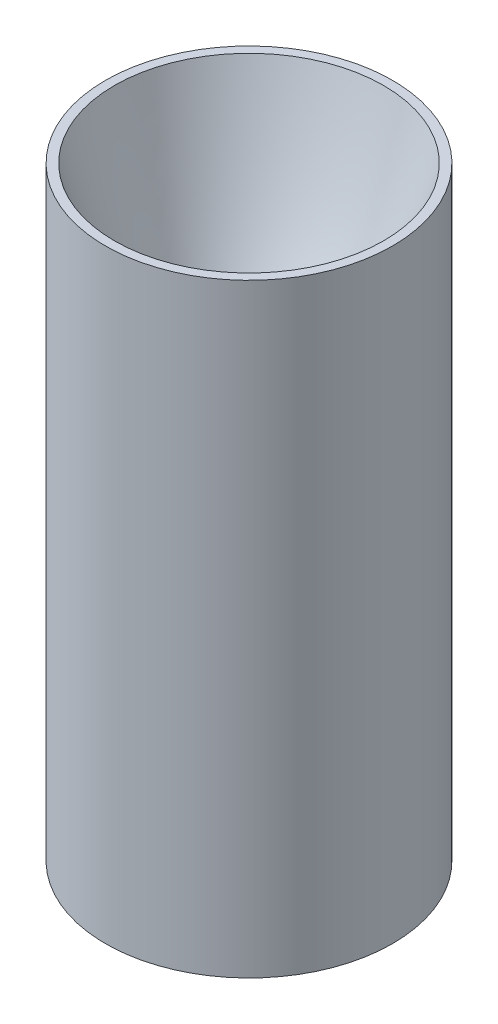
SolidWorks part; units mm, degrees
material "AISI 1020"
ref_plane "Front Plane" through (0, 0, 0) normal (0, 0, 1) x (1, 0, 0)
ref_plane "Top Plane" through (0, 0, 0) normal (0, 1, 0) x (1, 0, 0)
ref_plane "Right Plane" through (0, 0, 0) normal (1, 0, 0) x (0, 0, -1)
sketch "Sketch1" plane through (0, 0, 0) normal (0, 0, 1) x (1, 0, 0)
  line L0 (-0.0055, 165.816) -> (-0.0055, -134.6871) construction
  line L1 (71.7275, 109.9275) -> (76.49, 109.9275)
  line L4 (53.8815, -59.7275) -> (53.8815, -212.1275)
  line L9 (76.49, 109.9275) -> (76.49, -212.1275)
  line L10 (76.49, -212.1275) -> (53.8815, -212.1275)
  spline S0 degree 2 poles (26.7953, 6.5094) (49.2614, 34.6361) (71.7275, 109.9275) knots 0 0 0 1 1 1 construction
  spline S1 degree 2 poles (26.7953, 6.5094) (49.2614, 34.6361) (71.7275, 109.9275) knots 0 0 0 1 1 1
  spline S2 degree 4 poles (24.1269, -0.7179) (24.126, -0.7018) (24.1243, -0.6738) (24.121, -0.6546) (24.115, -0.5166) (24.1058, -0.4369) (24.0994, -0.1066) (24.0979, 0.0018) (24.102, 0.2678) (24.1085, 0.4272) (24.1205, 0.6469) (24.1414, 0.9016) (24.1752, 1.2027) (24.2265, 1.5422) (24.2905, 1.8812) (24.3671, 2.2165) (24.4563, 2.5494) (24.5577, 2.8783) (24.6716, 3.2035) (24.7972, 3.5238) (24.9353, 3.8398) (25.0841, 4.1494) (25.246, 4.4549) (25.4165, 4.7515) (25.6025, 5.0459) (25.7918, 5.3257) (26.0044, 5.6109) (26.1789, 5.8331) (26.3663, 6.0501) (26.5046, 6.2088) (26.757, 6.4728) (26.837, 6.5526) (27.1016, 6.806) (27.1881, 6.8783) (27.2854, 6.9667) (27.3038, 6.9803) (27.3264, 7.0004) knots 0 0 0 0 0 0.005192 0.010384 0.020768 0.041536 0.082569 0.102427 0.122284 0.142142 0.162 0.201716 0.241431 0.281147 0.320863 0.360578 0.400294 0.44001 0.479725 0.519441 0.559156 0.598872 0.638588 0.678303 0.718019 0.757735 0.79745 0.837166 0.857024 0.876882 0.916597 0.958047 0.979024 0.989512 1 1 1 1 1 construction
  spline S3 degree 4 poles (24.0991, 0.0002) (24.0991, 0.0361) (24.0996, 0.1103) (24.102, 0.2678) (24.1085, 0.4272) (24.1205, 0.6469) (24.1414, 0.9016) (24.1752, 1.2027) (24.2265, 1.5422) (24.2905, 1.8812) (24.3671, 2.2165) (24.4563, 2.5494) (24.5577, 2.8783) (24.6716, 3.2035) (24.7972, 3.5238) (24.9353, 3.8398) (25.0841, 4.1494) (25.246, 4.4549) (25.4165, 4.7515) (25.6025, 5.0459) (25.7918, 5.3257) (26.0044, 5.6109) (26.1789, 5.8331) (26.3663, 6.0501) (26.5046, 6.2088) (26.6704, 6.3823) (26.7445, 6.4586) (26.7953, 6.5094) knots 0.082569 0.082569 0.082569 0.082569 0.082569 0.102427 0.122284 0.142142 0.162 0.201716 0.241431 0.281147 0.320863 0.360578 0.400294 0.44001 0.479725 0.519441 0.559156 0.598872 0.638588 0.678303 0.718019 0.757735 0.79745 0.837166 0.857024 0.876882 0.916597 0.916597 0.916597 0.916597 0.916597
  spline S4 degree 4 poles (24.2082, 2.808) (24.2014, 2.7166) (24.1882, 2.5518) (24.1642, 2.1754) (24.1352, 1.6881) (24.1148, 1.1018) (24.103, 0.6556) (24.0988, 0.1104) (24.0988, -0.0999) (24.102, -0.543) (24.1083, -0.824) (24.1178, -1.1947) (24.1304, -1.5133) (24.1462, -1.8618) (24.1652, -2.1935) (24.1928, -2.6179) (24.2323, -3.1219) (24.3033, -3.8798) (24.4231, -4.8863) (24.5995, -6.0566) (24.8509, -7.385) (25.1518, -8.7034) (25.5018, -10.0095) (25.9004, -11.3017) (26.3469, -12.5779) (26.841, -13.8367) (27.3817, -15.076) (27.9685, -16.2944) (28.6001, -17.4898) (29.2765, -18.6611) (29.9954, -19.8056) (30.758, -20.9237) (31.4592, -21.8743) (32.0887, -22.6733) (32.6241, -23.3203) (33.0723, -23.8398) (33.5085, -24.3297) (33.9358, -24.7883) (34.2456, -25.1137) (34.6121, -25.4859) (34.7661, -25.6398) (35.1509, -26.0187) (35.4776, -26.3286) (35.905, -26.7273) (36.2395, -27.0242) (36.5192, -27.2707) (36.6465, -27.3798) (36.7148, -27.4387) (36.7496, -27.4686) knots 0 0 0 0 0 0.010393 0.020785 0.041571 0.062104 0.072371 0.082638 0.092575 0.102512 0.112449 0.122387 0.132324 0.142261 0.152198 0.162135 0.18201 0.201884 0.241633 0.281382 0.32113 0.360879 0.400628 0.440377 0.480126 0.519874 0.559623 0.599372 0.639121 0.67887 0.718618 0.758367 0.798116 0.81799 0.837865 0.857739 0.877613 0.897488 0.907425 0.917362 0.927629 0.937896 0.958429 0.979215 0.989607 0.994804 1 1 1 1 1 construction
  spline S5 degree 4 poles (24.0991, 0.0002) (24.0991, -0.0704) (24.0996, -0.2134) (24.102, -0.543) (24.1083, -0.824) (24.1178, -1.1947) (24.1304, -1.5133) (24.1462, -1.8618) (24.1652, -2.1935) (24.1928, -2.6179) (24.2323, -3.1219) (24.3033, -3.8798) (24.4231, -4.8863) (24.5995, -6.0566) (24.8509, -7.385) (25.1518, -8.7034) (25.5018, -10.0095) (25.9004, -11.3017) (26.3469, -12.5779) (26.841, -13.8367) (27.3817, -15.076) (27.9685, -16.2944) (28.6001, -17.4898) (29.2765, -18.6611) (29.9954, -19.8056) (30.758, -20.9237) (31.4592, -21.8743) (32.0887, -22.6733) (32.6241, -23.3203) (33.0723, -23.8398) (33.5085, -24.3297) (33.9358, -24.7883) (34.2456, -25.1137) (34.5369, -25.4095) (34.6364, -25.5098) (34.6863, -25.5597) knots 0.082638 0.082638 0.082638 0.082638 0.082638 0.092575 0.102512 0.112449 0.122387 0.132324 0.142261 0.152198 0.162135 0.18201 0.201884 0.241633 0.281382 0.32113 0.360879 0.400628 0.440377 0.480126 0.519874 0.559623 0.599372 0.639121 0.67887 0.718618 0.758367 0.798116 0.81799 0.837865 0.857739 0.877613 0.897488 0.907425 0.917362 0.917362 0.917362 0.917362 0.917362
  spline S6 degree 1 poles (34.6863, -25.5597) (43.2939, -34.1673) knots 0 0 1 1 construction
  spline S7 degree 1 poles (34.6863, -25.5597) (43.2939, -34.1673) knots 0 0 1 1
  spline S8 degree 4 poles (53.7724, -62.5352) (53.7792, -62.4464) (53.7924, -62.2737) (53.8104, -62.0016) (53.8309, -61.6599) (53.848, -61.2921) (53.8616, -60.9658) (53.8717, -60.5752) (53.8784, -60.2939) (53.8818, -59.8332) (53.8818, -59.6304) (53.8786, -59.1816) (53.8723, -58.9048) (53.8628, -58.5326) (53.8502, -58.2128) (53.8304, -57.7816) (53.8004, -57.281) (53.7562, -56.688) (53.6773, -55.8485) (53.5774, -55.0082) (53.4567, -54.1724) (53.2868, -53.1724) (53.0921, -52.1774) (52.8664, -51.1885) (52.61, -50.2075) (52.3293, -49.2331) (52.0243, -48.266) (51.6335, -47.1491) (51.1395, -45.8904) (50.5987, -44.651) (50.0121, -43.4327) (49.3801, -42.2371) (48.7041, -41.0662) (47.9845, -39.921) (47.2231, -38.8041) (46.5199, -37.8515) (45.8935, -37.0557) (45.3528, -36.4034) (44.9151, -35.8942) (44.5148, -35.447) (44.1815, -35.0846) (43.8739, -34.7603) (43.6741, -34.5515) (43.3653, -34.2383) (43.2159, -34.0889) (42.8277, -33.7066) (42.5041, -33.3998) (42.0741, -32.9986) (41.7412, -32.7033) (41.4607, -32.4559) (41.3338, -32.3472) (41.2653, -32.2883) (41.2305, -32.2583) knots 0 0 0 0 0 0.010393 0.020785 0.031178 0.041571 0.051838 0.062104 0.072371 0.082638 0.092575 0.102512 0.112449 0.122387 0.132324 0.142261 0.162135 0.18201 0.201884 0.241633 0.261507 0.281382 0.32113 0.360879 0.380754 0.400628 0.440377 0.480126 0.519874 0.559623 0.599372 0.639121 0.67887 0.718618 0.758367 0.798116 0.81799 0.837865 0.857739 0.877613 0.887551 0.897488 0.907425 0.917362 0.927629 0.937896 0.958429 0.979215 0.989607 0.994804 1 1 1 1 1 construction
  spline S9 degree 4 poles (53.8815, -59.7275) (53.8815, -59.657) (53.881, -59.5154) (53.8786, -59.1816) (53.8723, -58.9048) (53.8628, -58.5326) (53.8502, -58.2128) (53.8304, -57.7816) (53.8004, -57.281) (53.7562, -56.688) (53.6773, -55.8485) (53.5774, -55.0082) (53.4567, -54.1724) (53.2868, -53.1724) (53.0921, -52.1774) (52.8664, -51.1885) (52.61, -50.2075) (52.3293, -49.2331) (52.0243, -48.266) (51.6335, -47.1491) (51.1395, -45.8904) (50.5987, -44.651) (50.0121, -43.4327) (49.3801, -42.2371) (48.7041, -41.0662) (47.9845, -39.921) (47.2231, -38.8041) (46.5199, -37.8515) (45.8935, -37.0557) (45.3528, -36.4034) (44.9151, -35.8942) (44.5148, -35.447) (44.1815, -35.0846) (43.8739, -34.7603) (43.6741, -34.5515) (43.4444, -34.3185) (43.3438, -34.2172) (43.2939, -34.1673) knots 0.082638 0.082638 0.082638 0.082638 0.082638 0.092575 0.102512 0.112449 0.122387 0.132324 0.142261 0.162135 0.18201 0.201884 0.241633 0.261507 0.281382 0.32113 0.360879 0.380754 0.400628 0.440377 0.480126 0.519874 0.559623 0.599372 0.639121 0.67887 0.718618 0.758367 0.798116 0.81799 0.837865 0.857739 0.877613 0.887551 0.897488 0.907425 0.917362 0.917362 0.917362 0.917362 0.917362
  spline S10 degree 2 poles (36.8348, 6.4922) (58.683, 41.9569) (81.7275, 109.9275) knots 0.244621 0.244621 0.244621 0.999364 0.999364 0.999364 construction
  dimension "D1" = 24.1046
  dimension "D2" = 53.8871
  dimension "D3" = 152.4
  dimension "D4" = 322.055
  dimension "D5" = 4.7625
  dimension "D7" = 24.0991
  dimension "D8" = 26.7953
  dimension "D9" = 34.6863
  dimension "D10" = 0.0002
revolve "Revolve2" add sketch "Sketch1" angle 360 about L0
sketch "Sketch2" plane through (0, -212.1275, 0) normal (0, -1, 0) x (1, 0, 0)
  line L1 (65.2, 0) -> (65.2, -54.0399) construction
  circle A3 centre (0, 0) radius 65.2 construction
  dimension "D1" = 130.4
hole_wizard "3/8-24 Tapped Hole1" positions "Sketch3" profile "Sketch4" tap size "3/8-24" standard "ANSI Inch"
sketch "Sketch3" plane through (0, -212.1275, 0) normal (0, -1, 0) x (-1, 0, 0)
  point P0 (-65.2, 0)
sketch "Sketch4" plane through (65.2, -212.1275, 0) normal (1, 0, 0) x (0, 0, -1)
  line L0 (0, 0) -> (0, 27.5335)
  line L1 (0, 27.5335) -> (4.2164, 25)
  line L2 (4.2164, 25) -> (4.2164, 0)
  line L5 (4.2164, 0) -> (0, 0)
  line L10 (0, 27.5335) -> (-4.2164, 25) construction
  line L11 (0, -6.35) -> (0, 107.95) construction
  dimension "Tap Drill Dia." = 8.4328
  dimension "Tap Drill Depth" = 25
  dimension "Drill Angle" = 118
cosmetic thread "Hole Thread1" parameters "D1"=20, "D2"=9.525
sketch "Sketch5" plane through (0, 0, 0) normal (0, 0, 1) x (1, 0, 0)
  line L0 (0, -228.487) -> (-0.0055, 109.9275) construction
  line L1 (71.7275, 109.9275) -> (-71.7386, 109.9275) construction
pattern_circular "CirPattern1" count 8 over 360 about axis through (0, -228.487, 0) along (0, 1, 0) of "3/8-24 Tapped Hole1"
cosmetic thread "Hole Thread2" parameters "D1"=20, "D2"=9.525
cosmetic thread "Hole Thread3" parameters "D1"=20, "D2"=9.525
cosmetic thread "Hole Thread4" parameters "D1"=20, "D2"=9.525
cosmetic thread "Hole Thread5" parameters "D1"=20, "D2"=9.525
cosmetic thread "Hole Thread6" parameters "D1"=20, "D2"=9.525
cosmetic thread "Hole Thread7" parameters "D1"=20, "D2"=9.525
cosmetic thread "Hole Thread8" parameters "D1"=20, "D2"=9.525
sketch "Sketch8" plane through (0, -212.1275, 0) normal (0, -1, 0) x (1, 0, 0)
  circle A0 centre (0, 0) radius 53.8815 construction
  circle A1 centre (0, 0) radius 76.49 construction
  circle A2 centre (0, 0) radius 65.2002 construction
  point P6 (0, 0)
  dimension "D1" = 107.7631
  dimension "D2" = 130.4004
  dimension "D3" = 152.98
